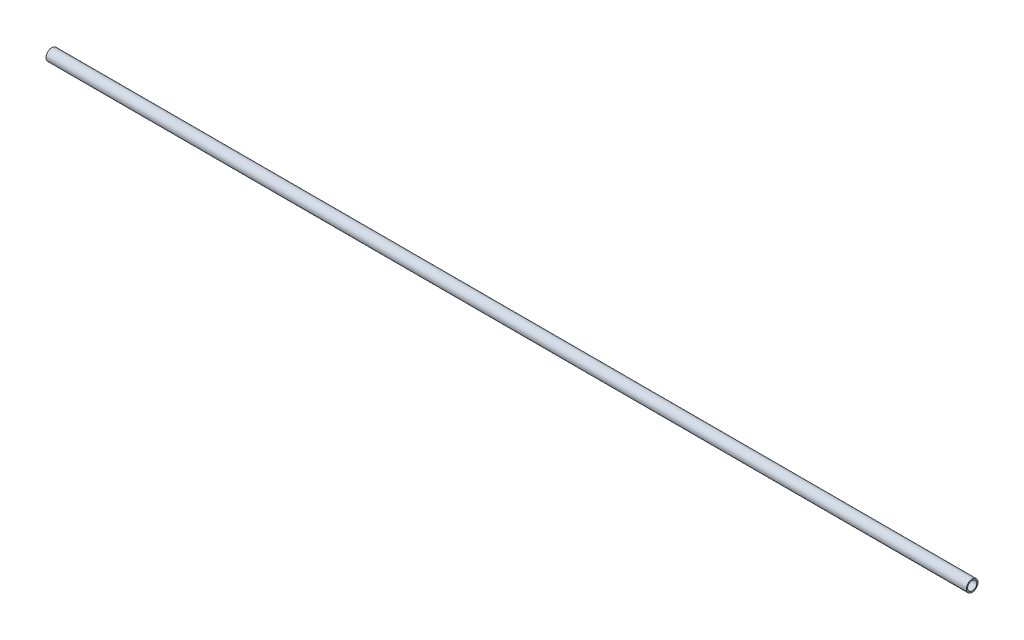
SolidWorks part; units mm, degrees
ref_plane "Alzado" through (0, 0, 0) normal (0, 0, 1) x (1, 0, 0)
ref_plane "Planta" through (0, 0, 0) normal (0, 1, 0) x (1, 0, 0)
ref_plane "Vista lateral" through (0, 0, 0) normal (1, 0, 0) x (0, 0, -1)
sketch "Croquis1" plane through (0, 0, 0) normal (1, 0, 0) x (0, 0, -1)
  circle A0 centre (0, 0) radius 19
  circle A1 centre (0, 0) radius 15
extrude "Saliente-Extruir1" add sketch "Croquis1" along normal blind 3000
